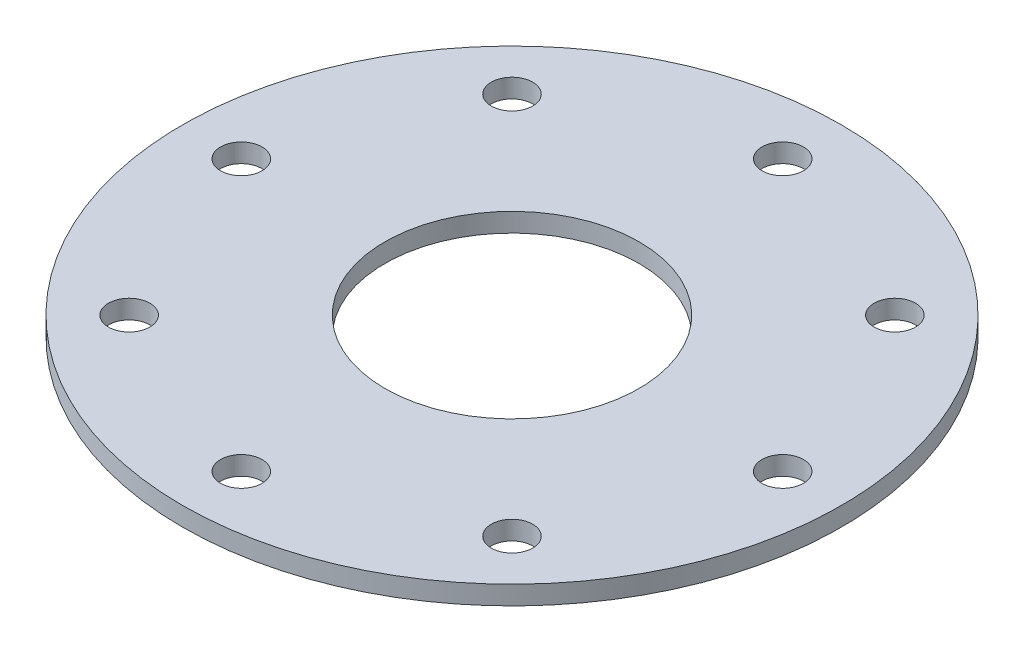
SolidWorks part; units mm, degrees
material "AISI 304"
ref_plane "Спереди" through (0, 0, 0) normal (0, 0, 1) x (1, 0, 0)
ref_plane "Сверху" through (0, 0, 0) normal (0, 1, 0) x (1, 0, 0)
ref_plane "Справа" through (0, 0, 0) normal (1, 0, 0) x (0, 0, -1)
sketch "Эскиз1" plane through (0, 0, 0) normal (0, 1, 0) x (1, 0, 0)
  line L0 (0, 0) -> (70, 0) construction
  circle A0 centre (0, 0) radius 70
  circle A1 centre (0, 0) radius 27
  circle A2 centre (0, 0) radius 57.5 construction
  circle A3 centre (57.5, 0) radius 4.4
  circle A4 centre (40.6586, -40.6586) radius 4.4
  circle A5 centre (0, -57.5) radius 4.4
  circle A6 centre (-40.6586, -40.6586) radius 4.4
  circle A7 centre (-57.5, 0) radius 4.4
  circle A8 centre (-40.6586, 40.6586) radius 4.4
  circle A9 centre (0, 57.5) radius 4.4
  circle A10 centre (40.6586, 40.6586) radius 4.4
  dimension "D1" = 140
  dimension "D2" = 54
  dimension "D3" = 115
  dimension "D4" = 8.8
  dimension "D5" = 8
extrude "Бобышка-Вытянуть1" add sketch "Эскиз1" along normal blind 4
equation "\"Диаметр отверстия\"= 8мм"
equation "\"Толщина крышки верхней обоймы\"= 4мм"
equation "\"D4@Эскиз1\"=\"Диаметр отверстия\" + 0.8мм"
equation "\"D1@Бобышка-Вытянуть1\"=\"Толщина крышки верхней обоймы\""
